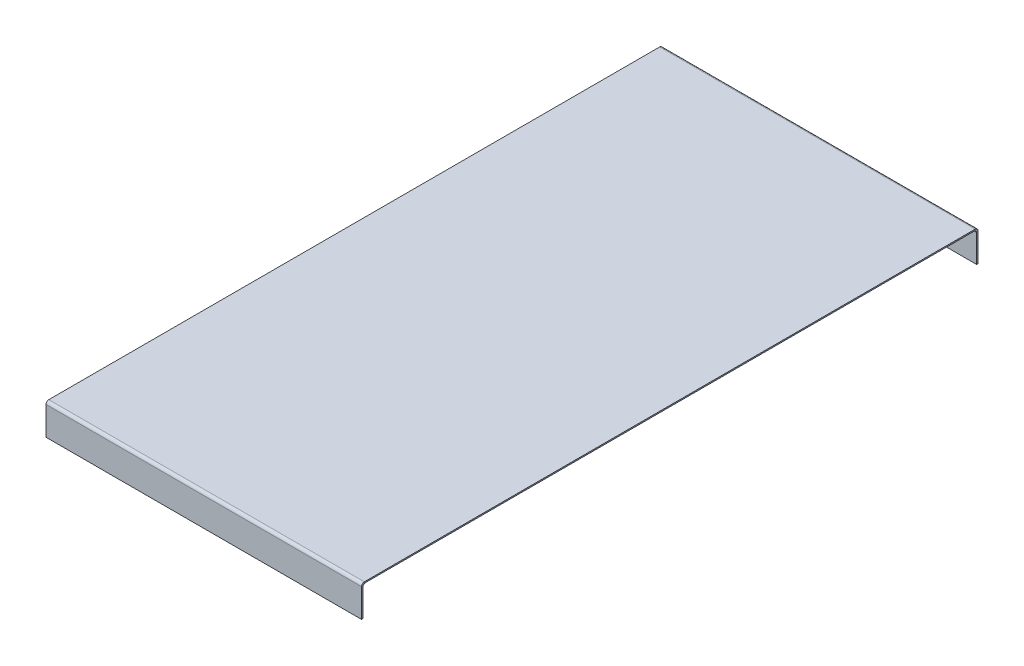
SolidWorks part; units mm, degrees
ref_plane "Front Plane" through (0, 0, 0) normal (0, 0, 1) x (1, 0, 0)
ref_plane "Top Plane" through (0, 0, 0) normal (0, 1, 0) x (1, 0, 0)
ref_plane "Right Plane" through (0, 0, 0) normal (1, 0, 0) x (0, 0, -1)
sketch "Sketch1" plane through (0, 0, 0) normal (1, 0, 0) x (0, 0, -1)
  line L0 (-25.7971, -87.4593) -> (-25.7971, -65.2293)
  line L1 (-25.7971, -65.2293) -> (413.8129, -65.2293)
  line L2 (413.8129, -65.2293) -> (413.8129, -87.5493)
  line L3 (413.8129, -87.5493) -> (412.8129, -87.5493)
  line L4 (412.8129, -87.5493) -> (412.8129, -66.1303)
  line L5 (412.8129, -66.1303) -> (-24.7971, -66.1303)
  line L6 (-24.7971, -66.1303) -> (-24.7971, -87.4593)
  line L7 (-24.7971, -87.4593) -> (-25.7971, -87.4593)
  dimension "D1" = 1
  dimension "D2" = 0.901
  dimension "D3" = 439.61
  dimension "D4" = 22.23
  dimension "D5" = 1
  dimension "D6" = 22.32
extrude "Boss-Extrude1" add sketch "Sketch1" along normal blind 225
fillet "Fillet1" radius 2 2 edges at (112.5, -65.2293, -413.8129) (112.5, -65.2293, 25.7971)
fillet "Fillet2" radius 2 2 edges at (112.5, -66.1303, 24.7971) (112.5, -66.1303, -412.8129)
